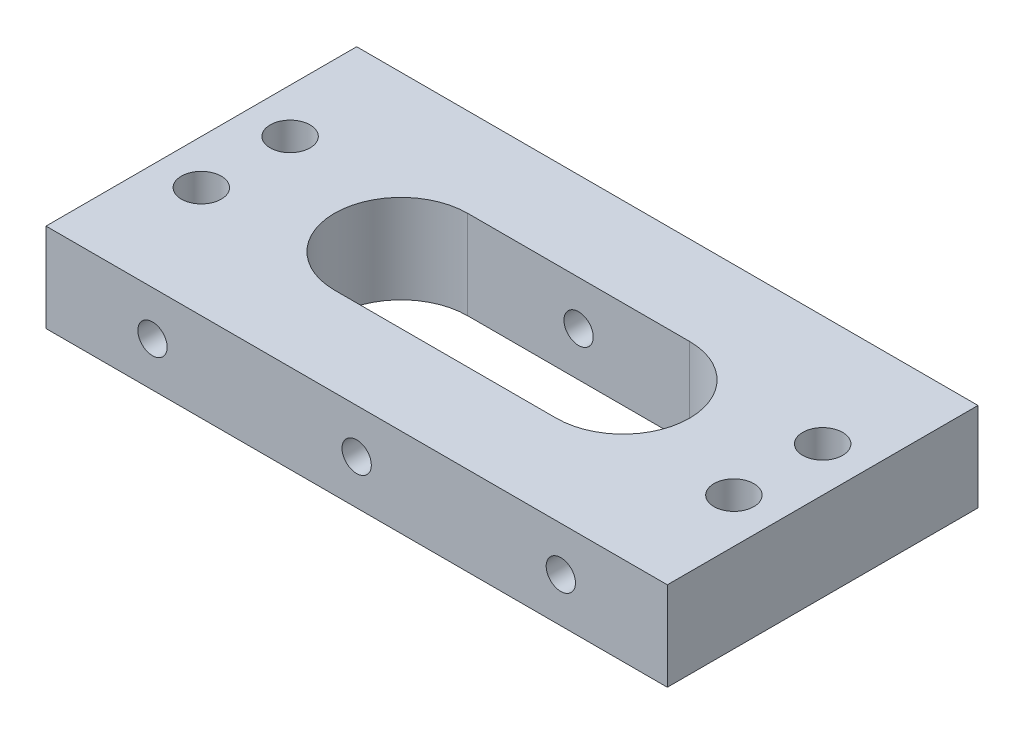
SolidWorks part; units mm, degrees
material "7079 Alloy"
ref_plane "Front Plane" through (0, 0, 0) normal (0, 0, 1) x (1, 0, 0)
ref_plane "Top Plane" through (0, 0, 0) normal (0, 1, 0) x (1, 0, 0)
ref_plane "Right Plane" through (0, 0, 0) normal (1, 0, 0) x (0, 0, -1)
sketch "Sketch1" plane through (0, 0, 0) normal (0, 1, 0) x (1, 0, 0)
  line L1 (35, -17.5) -> (-35, -17.5)
  line L2 (35, -17.5) -> (35, 17.5)
  line L3 (35, 17.5) -> (-35, 17.5)
  line L4 (-35, -17.5) -> (-35, 17.5)
  line L5 (35, -17.5) -> (-35, 17.5) construction
  line L6 (35, 17.5) -> (-35, -17.5) construction
  point P0 (0, 0)
  dimension "D1" = 70
  dimension "D2" = 35
extrude "Boss-Extrude1" add sketch "Sketch1" along normal blind 10
sketch "Sketch2" plane through (0, 0, 17.5) normal (0, 0, 1) x (1, 0, 0)
  line L0 (-35, 5) -> (35, 5) construction
  line L1 (-35, 10) -> (-35, 0) construction
  line L2 (35, 10) -> (35, 0) construction
  line L3 (0, 5) -> (0, 10) construction
  line L4 (-35, 10) -> (35, 10) construction
  circle A0 centre (-23, 5) radius 1.65
  circle A1 centre (0, 5) radius 1.65
  circle A2 centre (23, 5) radius 1.65
  dimension "D1" = 3.3
  dimension "D2" = 23
extrude "Cut-Extrude1" cut sketch "Sketch2" against normal blind 10
sketch "Sketch3" plane through (0, 10, 0) normal (0, 1, 0) x (1, 0, 0)
  line L0 (-12.5, 0) -> (12.5, 0) construction
  line L1 (-12.5, 7.5) -> (12.5, 7.5)
  line L2 (-12.5, -7.5) -> (12.5, -7.5)
  arc A0 (-12.5, 7.5) -> (-12.5, -7.5) centre (-12.5, 0) ccw
  arc A1 (12.5, -7.5) -> (12.5, 7.5) centre (12.5, 0) ccw
  point P2 (0, 0)
  dimension "D2" = 7.5
  dimension "D1" = 25
extrude "Cut-Extrude2" cut sketch "Sketch3" against normal blind 10
sketch "Sketch4" plane through (0, 10, 0) normal (0, 1, 0) x (1, 0, 0)
  line L0 (0, 0) -> (0, 17.5) construction
  line L1 (35, 17.5) -> (-35, 17.5) construction
  line L2 (0, 0) -> (-35, 0) construction
  line L3 (-35, 17.5) -> (-35, -17.5) construction
  circle A0 centre (-30, -5) radius 2.25
  circle A1 centre (-30, 5) radius 2.25
  circle A2 centre (30, -5) radius 2.25
  circle A3 centre (30, 5) radius 2.25
  dimension "D3" = 4.5
  dimension "D1" = 10
  dimension "D2" = 60
extrude "Cut-Extrude3" cut sketch "Sketch4" against normal blind 10
ref_plane "Plane1" through (0, 0, 0) normal (0, 0, 1) x (1, 0, 0)
mirror "Mirror1" about plane through (0, 0, 0) normal (0, 0, 1) of "Cut-Extrude1"
